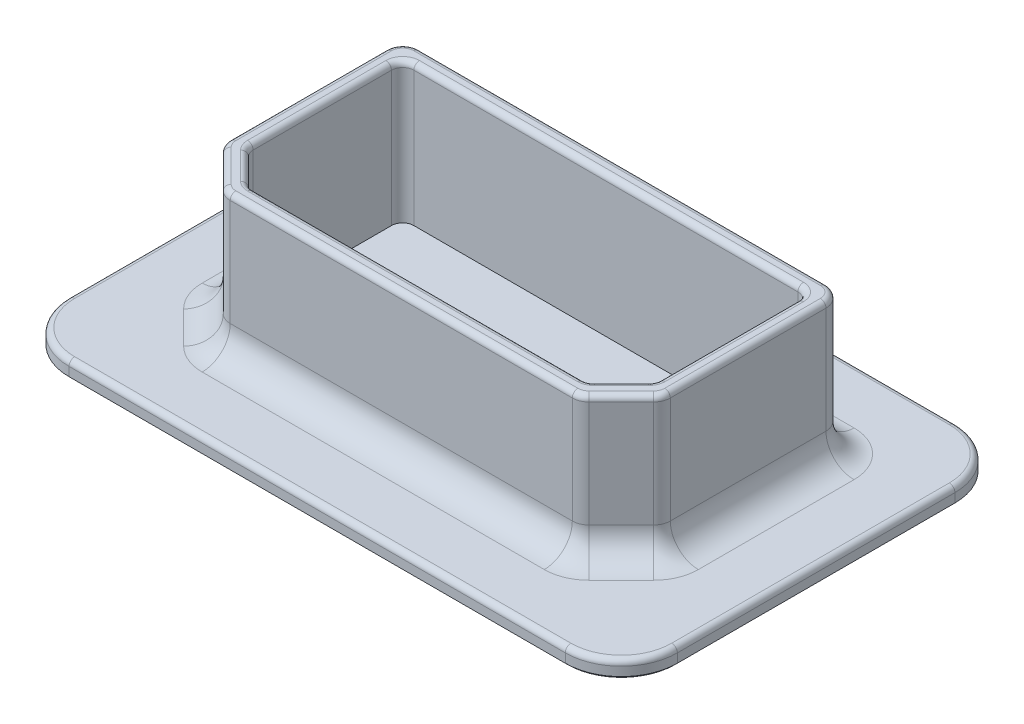
SolidWorks part; units mm, degrees
ref_plane "前视基准面" through (0, 0, 0) normal (0, 0, 1) x (1, 0, 0)
ref_plane "上视基准面" through (0, 0, 0) normal (0, 1, 0) x (1, 0, 0)
ref_plane "右视基准面" through (0, 0, 0) normal (1, 0, 0) x (0, 0, -1)
other "Configuration Table"
sketch "草图1" plane through (0, 0, 0) normal (0, 1, 0) x (1, 0, 0)
  line L0 (-3, 36.5) -> (75.5, 36.5)
  line L1 (0, 0) -> (72.5, 0)
  line L2 (0, 0) -> (0, 33.5)
  line L3 (0, 33.5) -> (72.5, 33.5)
  line L4 (72.5, 0) -> (72.5, 33.5)
  line L5 (75.5, -3) -> (75.5, 36.5)
  line L6 (-3, -3) -> (75.5, -3)
  line L7 (-3, -3) -> (-3, 36.5)
  dimension "D1" = 72.5
  dimension "D2" = 33.5
  dimension "D3" = 3
extrude "凸台-拉伸1" add sketch "草图1" along normal blind 25
sketch "草图2" plane through (0, 0, 0) normal (0, -1, 0) x (-1, 0, 0)
  line L14 (-90.5, 51.5) -> (-90.5, -18)
  line L15 (18, 51.5) -> (-90.5, 51.5)
  line L16 (18, -18) -> (18, 51.5)
  line L17 (-90.5, -18) -> (18, -18)
  line L18 (-90.5, 51.5) -> (-90.5, -18)
  line L19 (18, 51.5) -> (-90.5, 51.5)
  line L20 (18, -18) -> (18, 51.5)
  line L21 (-90.5, -18) -> (18, -18)
  dimension "D1" = 15
extrude "凸台-拉伸2" add sketch "草图2" along normal blind 3
fillet "圆角1" radius 10 4 edges at (-18, -1.5, 18) (-18, -1.5, -51.5) (90.5, -1.5, -51.5) (90.5, -1.5, 18)
chamfer "倒角1" distance 6 angle 45 2 edges at (72.5, 12.5, 0) (0, 12.5, 0)
chamfer "倒角2" distance 7.5 angle 45 2 edges at (-3, 12.5, 3) (75.5, 12.5, 3)
fillet "圆角2" radius 2 6 edges at (0, 12.5, -33.5) (72.5, 12.5, -33.5) (72.5, 12.5, -6) (0, 12.5, -6) (6, 12.5, 0) (66.5, 12.5, 0)
fillet "圆角3" radius 3 6 edges at (75.5, 12.5, -4.5) (68, 12.5, 3) (4.5, 12.5, 3) (-3, 12.5, -4.5) (-3, 12.5, -36.5) (75.5, 12.5, -36.5)
fillet "圆角4" radius 5 12 edges at (-2.1213, 0, -35.6213) (36.25, 0, -36.5) (74.6213, 0, -35.6213) (75.5, 0, -19.6213) (75.2716, 0, -4.5946) (71.75, 0, -0.75) (67.9054, 0, 2.7716) (36.25, 0, 3) (4.5946, 0, 2.7716) (0.75, 0, -0.75) (-2.7716, 0, -4.5946) (-3, 0, -19.6213)
fillet "圆角5" radius 1 24 edges at (0.1522, 25, -6.0631) (3, 25, -3) (6.0631, 25, -0.1522) (36.25, 25, 0) (66.4369, 25, -0.1522) (69.5, 25, -3) (72.3478, 25, -6.0631) (72.5, 25, -19.1642) (71.9142, 25, -32.9142) (36.25, 25, -33.5) (0.5858, 25, -32.9142) (0, 25, -19.1642) (67.9054, 25, 2.7716) (36.25, 25, 3) (4.5946, 25, 2.7716) (0.75, 25, -0.75) (-2.7716, 25, -4.5946) (-3, 25, -19.6213) (-2.1213, 25, -35.6213) (36.25, 25, -36.5) (74.6213, 25, -35.6213) (75.5, 25, -19.6213) (75.2716, 25, -4.5946) (71.75, 25, -0.75)
fillet "圆角6" radius 1 8 edges at (-15.0711, 0, -48.5711) (36.25, 0, -51.5) (87.5711, 0, -48.5711) (90.5, 0, -16.75) (87.5711, 0, 15.0711) (36.25, 0, 18) (-15.0711, 0, 15.0711) (-18, 0, -16.75)
chamfer "倒角3" distance 0.4 angle 45 8 edges at (87.5711, -3, 15.0711) (90.5, -3, -16.75) (87.5711, -3, -48.5711) (36.25, -3, -51.5) (-15.0711, -3, -48.5711) (-18, -3, -16.75) (-15.0711, -3, 15.0711) (36.25, -3, 18)
